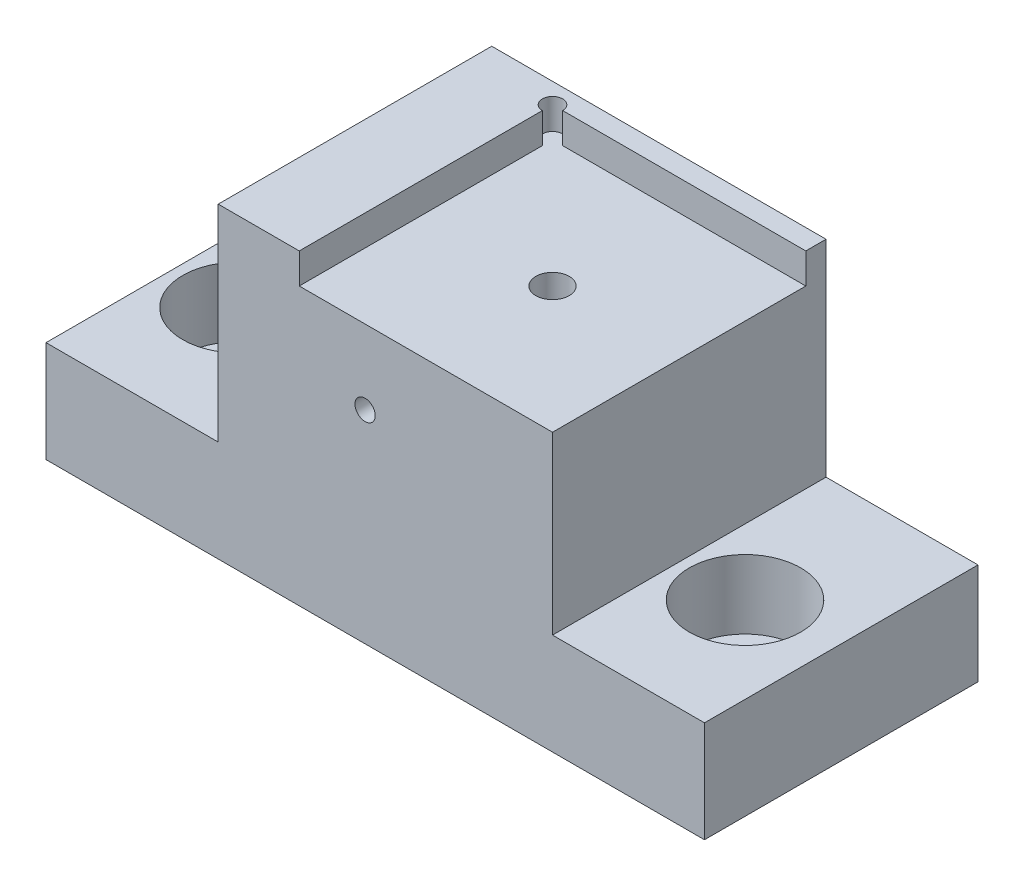
SolidWorks part; units mm, degrees
material "6061 合金"
ref_plane "前视基准面" through (0, 0, 0) normal (0, 0, 1) x (1, 0, 0)
ref_plane "上视基准面" through (0, 0, 0) normal (0, 1, 0) x (1, 0, 0)
ref_plane "右视基准面" through (0, 0, 0) normal (1, 0, 0) x (0, 0, -1)
sketch "草图1" plane through (0, 0, 0) normal (0, 1, 0) x (1, 0, 0)
  line L1 (-14.5, 14.5) -> (14.5, 14.5)
  line L2 (-14.5, 14.5) -> (-14.5, -14.5)
  line L3 (-14.5, -14.5) -> (14.5, -14.5)
  line L4 (14.5, 14.5) -> (14.5, -14.5)
  line L5 (-14.5, 14.5) -> (14.5, -14.5) construction
  line L6 (-14.5, -14.5) -> (14.5, 14.5) construction
  point P0 (0, 0)
  dimension "D1" = 29
  dimension "D2" = 29
extrude "凸台-拉伸1" add sketch "草图1" along normal blind 5
sketch "草图2" plane through (0, 5, 0) normal (0, -1, 0) x (1, 0, 0)
  line L1 (-12.5, 12.5) -> (12.5, 12.5)
  line L2 (-12.5, 12.5) -> (-12.5, -12.5)
  line L3 (-12.5, -12.5) -> (12.5, -12.5)
  line L4 (12.5, 12.5) -> (12.5, -12.5)
  line L5 (-12.5, 12.5) -> (12.5, -12.5) construction
  line L6 (-12.5, -12.5) -> (12.5, 12.5) construction
  point P0 (0, 0)
  dimension "D1" = 25
  dimension "D2" = 25
extrude "切除-拉伸1" cut sketch "草图2" along normal blind 3
sketch "草图3" plane through (0, 0, 0) normal (0, -1, 0) x (-1, 0, 0)
  line L1 (-14.5, -14.5) -> (20.5, -14.5)
  line L2 (-14.5, -14.5) -> (-14.5, 14.5)
  line L3 (-14.5, 14.5) -> (20.5, 14.5)
  line L4 (20.5, -14.5) -> (20.5, 14.5)
  dimension "D1" = 29
  dimension "D2" = 35
extrude "拉到底部滑块" add sketch "草图3" along normal up to surface (25.3412 mm away)
sketch "草图5" plane through (0, 2, 0) normal (0, 1, 0) x (1, 0, 0)
  circle A0 centre (0, 0) radius 2.1526
hole_wizard "M4 螺纹孔1" positions "3D草图1" profile "草图6" tap size "M4" standard "GB"
sketch3d "3D草图1"
  point P0 (0, 2, 0)
sketch "草图6" plane through (0, 2, 0) normal (1, 0, 0) x (0, 0, 1)
  line L0 (0, 0) -> (0, 11.0914)
  line L1 (0, 11.0914) -> (1.65, 10.1)
  line L2 (1.65, 10.1) -> (1.65, 0)
  line L5 (1.65, 0) -> (0, 0)
  line L10 (0, 11.0914) -> (-1.65, 10.1) construction
  line L11 (0, -6.35) -> (0, 107.95) construction
  dimension "螺纹孔钻头直径" = 3.3
  dimension "螺纹孔钻头深度" = 10.1
  dimension "导头角度" = 118
cosmetic thread "孔螺蚊线1" parameters "D1"=8, "D2"=4
sketch "草图9" plane through (0, 5, 0) normal (0, 1, 0) x (1, 0, 0)
  circle A0 centre (-12.5, 12.5) radius 1
extrude "切除-拉伸2" cut sketch "草图9" against normal up to surface (3 mm away) up to face at (0, 2, 1.65)
sketch "草图11" plane through (-14.5, 0, 0) normal (-1, 0, 0) x (0, 0, 1)
  line L4 (-14.5, 0) -> (14.5, 0)
  line L5 (14.5, 0) -> (14.5, 5)
  line L6 (14.5, 5) -> (-14.5, 5)
  line L7 (-14.5, 5) -> (-14.5, 0)
  line L8 (-14.5, 0) -> (14.5, 0)
  line L9 (14.5, 0) -> (14.5, 5)
  line L10 (14.5, 5) -> (-14.5, 5)
  line L11 (-14.5, 5) -> (-14.5, 0)
  dimension "D1" = 0
extrude "凸台-拉伸4" add sketch "草图11" along normal up to surface (6 mm away) up to face at (-20.5, -12.6706, 0)
sketch "草图17" plane through (0, 5, 0) normal (0, 1, 0) x (1, 0, 0)
  line L0 (-20.5, -14.5) -> (14.5, -14.5) construction
  line L1 (14.5, -14.5) -> (14.5, 14.5) construction
  line L2 (-20.5, -14.5) -> (14.5, -14.5)
  line L3 (14.5, -14.5) -> (14.5, 14.5)
  line L4 (-20.5, -12.5) -> (12.5, -12.5)
  line L5 (12.5, -12.5) -> (12.5, 14.5)
  line L6 (12.5, 14.5) -> (14.5, 14.5)
  line L7 (-20.5, -12.5) -> (-20.5, -14.5)
  dimension "D1" = 2
extrude "切除-拉伸8" cut sketch "草图17" against normal through all
sketch "草图18" plane through (0, -25.3412, 0) normal (0, -1, 0) x (1, 0, 0)
  line L0 (0, 0) -> (-6, 0) construction
  line L1 (16.5, 0) -> (-16.5, 0) construction
  line L2 (-6, 0) -> (-6, 12.5) construction
  line L3 (12.5, 12.5) -> (-20.5, 12.5) construction
  circle A0 centre (-6, 0) radius 1.512
  dimension "D1" = 6
sketch "草图19" plane through (0, -25.3412, 0) normal (0, -1, 0) x (-1, 0, 0)
  line L0 (-12.5, -12.5) -> (20.5, -12.5) construction
  line L1 (46, -12.5) -> (-34, -12.5)
  line L2 (46, -12.5) -> (46, 12.5)
  line L3 (46, 12.5) -> (-34, 12.5)
  line L4 (-34, -12.5) -> (-34, 12.5)
  line L5 (46, -12.5) -> (-34, 12.5) construction
  line L6 (46, 12.5) -> (-34, -12.5) construction
  point P0 (6, 0)
  dimension "D1" = 80
extrude "凸台-拉伸5" add sketch "草图19" against normal blind 10
sketch "草图21" plane through (0, -15.3412, 0) normal (0, 1, 0) x (1, 0, 0)
  line L0 (-6, 0) -> (-31, 0)
  line L3 (-16.5, 0) -> (16.5, 0) construction
  line L4 (-6, 0) -> (19, 0)
  dimension "D1" = 25
  dimension "D2" = 25
hole_wizard "打孔尺寸(%根据)内六角圆柱头螺钉的类型1" positions "3D草图2" profile "草图22" counterbore size "M6" standard "GB"
sketch3d "3D草图2"
  point P0 (-31, -15.3412, 0)
  point P3 (19, -15.3412, 0)
sketch "草图22" plane through (-31, -15.3412, 0) normal (1, 0, 0) x (0, 0, 1)
  line L0 (0, 0) -> (0, 12.0828)
  line L1 (0, 12.0828) -> (3.3, 10.1)
  line L2 (3.3, 10.1) -> (3.3, 6.8)
  line L3 (3.3, 6.8) -> (5.5, 6.8)
  line L4 (5.5, 6.8) -> (5.5, 0)
  line L5 (5.5, 0) -> (0, 0)
  line L10 (0, 12.0828) -> (-3.3, 10.1) construction
  line L11 (0, -6.35) -> (0, 107.95) construction
  dimension "孔直径" = 6.6
  dimension "孔深度" = 10.1
  dimension "柱形沉头孔直径" = 11
  dimension "柱形沉头孔深度" = 6.8
  dimension "导头角度" = 118
sketch "草图23" plane through (0, 0, -12.5) normal (0, 0, -1) x (-1, 0, 0)
  line L1 (-34, -15.3412) -> (46, -15.3412)
  line L2 (-34, -15.3412) -> (-34, -25.3412)
  line L3 (-34, -25.3412) -> (46, -25.3412)
  line L4 (46, -15.3412) -> (46, -25.3412)
extrude "凸台-拉伸6" add sketch "草图23" along normal up to surface (2 mm away) up to face at (-4, -10.1706, -14.5)
sketch "草图24" plane through (-46, 0, 0) normal (-1, 0, 0) x (0, 0, 1)
  line L4 (-14.5, -25.3412) -> (12.5, -25.3412)
  line L5 (12.5, -25.3412) -> (12.5, -15.3412)
  line L6 (12.5, -15.3412) -> (-14.5, -15.3412)
  line L7 (-14.5, -15.3412) -> (-14.5, -25.3412)
  line L8 (-14.5, -25.3412) -> (12.5, -25.3412)
  line L9 (12.5, -25.3412) -> (12.5, -15.3412)
  line L10 (12.5, -15.3412) -> (-14.5, -15.3412)
  line L11 (-14.5, -15.3412) -> (-14.5, -25.3412)
  dimension "D1" = 0
extrude "切除-拉伸9" cut sketch "草图24" against normal blind 2
sketch "草图25" plane through (0, -25.3412, 0) normal (0, -1, 0) x (1, 0, 0)
  line L0 (-31, 0) -> (-21, 0) construction
  line L1 (-6, 0) -> (-31, 0) construction
  line L2 (19, 0) -> (9, 0) construction
  line L3 (-6, 0) -> (19, 0) construction
  dimension "D1" = 10
hole_wizard "大小mm 暗销孔1" positions "3D草图3" profile "草图26" hole size "Ø4.0" standard "GB"
sketch3d "3D草图3"
  point P0 (-21, -25.3412, 0)
sketch "草图26" plane through (-21, -25.3412, 0) normal (1, 0, 0) x (0, 0, -1)
  line L0 (0, 0) -> (0, 6.2017)
  line L1 (0, 6.2017) -> (2, 5)
  line L2 (2, 5) -> (2, 0)
  line L5 (2, 0) -> (0, 0)
  line L10 (0, 6.2017) -> (-2, 5) construction
  line L11 (0, -6.35) -> (0, 107.95) construction
  dimension "孔直径" = 4
  dimension "孔深度" = 5
  dimension "导头角度" = 118
sketch "草图27" plane through (0, -25.3412, 0) normal (0, -1, 0) x (1, 0, 0)
  line L0 (8.5, 0) -> (9.5, 0) construction
  line L1 (8.5, 2) -> (9.5, 2)
  line L2 (8.5, -2) -> (9.5, -2)
  arc A0 (8.5, 2) -> (8.5, -2) centre (8.5, 0) ccw
  arc A1 (9.5, -2) -> (9.5, 2) centre (9.5, 0) ccw
  circle A2 centre (-21, 0) radius 2 construction
  point P2 (9, 0)
  dimension "D1" = 1
extrude "切除-拉伸10" cut sketch "草图27" against normal blind 5
sketch "草图28" plane through (0, 0, 12.5) normal (0, 0, 1) x (1, 0, 0)
  line L0 (-6, -25.3412) -> (-6, -5.3412) construction
  circle A0 centre (-6, -5.3412) radius 1
  dimension "D1" = 20
extrude "切除-拉伸11" cut sketch "草图28" against normal blind 2
hole_wizard "M6 螺纹孔1" positions "3D草图4" profile "草图29" tap size "M6" standard "GB"
sketch3d "3D草图4"
  point P0 (-6, -25.3412, 0)
sketch "草图29" plane through (-6, -25.3412, 0) normal (1, 0, 0) x (0, 0, -1)
  line L0 (0, 0) -> (0, 11.5022)
  line L1 (0, 11.5022) -> (2.5, 10)
  line L2 (2.5, 10) -> (2.5, 0)
  line L5 (2.5, 0) -> (0, 0)
  line L10 (0, 11.5022) -> (-2.5, 10) construction
  line L11 (0, -6.35) -> (0, 107.95) construction
  dimension "螺纹孔钻头直径" = 5
  dimension "螺纹孔钻头深度" = 10
  dimension "导头角度" = 118
cosmetic thread "孔螺蚊线2" parameters "D1"=10, "D2"=6
sketch "草图30" plane through (0, -25.3412, 0) normal (0, -1, 0) x (-1, 0, 0)
  circle A0 centre (21, 0) radius 2
  circle A1 centre (-9, 0) radius 2
extrude "切除-拉伸12" cut sketch "草图31" against normal through all and the other way through all
sketch "草图31" plane through (-6.0032, 14.6588, 10.4718) normal (0, 0, 1) x (1, 0, 0)
  line L13 (10.1171, -31.7) -> (8.8541, -31.7)
  line L14 (8.8541, -31.7) -> (6.0752, -36.5641)
  line L15 (6.0752, -36.5641) -> (6.5318, -36.825)
  line L16 (6.5318, -36.825) -> (10.275, -36.825)
  line L17 (10.275, -38.325) -> (9.525, -38.325)
  line L18 (9.525, -38.325) -> (9.525, -40)
  line L19 (-9.7761, -40) -> (-9.7761, -38.0744)
  line L20 (-9.7761, -38.0744) -> (-10.5261, -38.0744)
  line L21 (-10.5261, -36.5744) -> (-6.5013, -36.5744)
  line L22 (-6.5013, -36.5744) -> (-6.5013, -36.3244)
  line L23 (-6.5013, -36.3244) -> (-9.1432, -31.7)
  line L24 (-9.1432, -31.7) -> (-10.3692, -31.7)
  line L25 (-10.3692, -30.2) -> (10.1171, -30.2)
  line L26 (-9.7761, -40) -> (9.525, -40)
  arc A4 (10.1171, -31.7) -> (10.1171, -30.2) centre (10.1171, -30.95) ccw
  arc A5 (10.275, -38.325) -> (10.275, -36.825) centre (10.275, -37.575) ccw
  arc A6 (-10.5261, -36.5744) -> (-10.5261, -38.0744) centre (-10.5261, -37.3244) ccw
  arc A7 (-10.3692, -30.2) -> (-10.3692, -31.7) centre (-10.3692, -30.95) ccw
sketch "草图32" plane through (-44, 0, 0) normal (-1, 0, 0) x (0, 0, 1)
  line L4 (-14.5, -15.3412) -> (-14.5, -25.3412)
  line L5 (-14.5, -25.3412) -> (12.5, -25.3412)
  line L6 (12.5, -25.3412) -> (12.5, -15.3412)
  line L7 (12.5, -15.3412) -> (-14.5, -15.3412)
  line L8 (-14.5, -15.3412) -> (-14.5, -25.3412)
  line L9 (-14.5, -25.3412) -> (12.5, -25.3412)
  line L10 (12.5, -25.3412) -> (12.5, -15.3412)
  line L11 (12.5, -15.3412) -> (-14.5, -15.3412)
  dimension "D1" = 0
extrude "切除-拉伸13" cut sketch "草图32" against normal blind 6.5
sketch "草图33" plane through (34, 0, 0) normal (1, 0, 0) x (0, 0, -1)
  line L4 (-12.5, -25.3412) -> (14.5, -25.3412)
  line L5 (14.5, -25.3412) -> (14.5, -15.3412)
  line L6 (14.5, -15.3412) -> (-12.5, -15.3412)
  line L7 (-12.5, -15.3412) -> (-12.5, -25.3412)
  line L8 (-12.5, -25.3412) -> (14.5, -25.3412)
  line L9 (14.5, -25.3412) -> (14.5, -15.3412)
  line L10 (14.5, -15.3412) -> (-12.5, -15.3412)
  line L11 (-12.5, -15.3412) -> (-12.5, -25.3412)
  dimension "D1" = 0
extrude "切除-拉伸14" cut sketch "草图33" against normal blind 6.5
sketch "草图34" plane through (0, -25.3412, 0) normal (0, -1, 0) x (1, 0, 0)
  line L0 (-21, 0) -> (-21, -8) construction
  line L2 (9, -8) -> (9, 0) construction
  line L4 (-21, 0) -> (-21, 8) construction
  circle A0 centre (-21, -8) radius 2
  circle A1 centre (9, -8) radius 2
  circle A2 centre (-21, 8) radius 2
sketch "草图35" plane through (0, -25.3412, 0) normal (0, -1, 0) x (1, 0, 0)
  line L0 (8.5, -8) -> (9.5, -8) construction
  line L2 (8.5, -6) -> (9.5, -6)
  line L3 (8.5, -10) -> (9.5, -10)
  line L4 (9, -8) -> (9, 0) construction
  arc A0 (8.5, -6) -> (8.5, -10) centre (8.5, -8) ccw
  arc A1 (9.5, -10) -> (9.5, -6) centre (9.5, -8) ccw
  circle A2 centre (-21, 0) radius 2 construction
  point P5 (9, -8)
  dimension "D1" = 1
extrude "切除-拉伸15" cut sketch "草图35" against normal up to surface (5 mm away) up to face at (9, -20.3412, 0)
hole_wizard "大小mm 暗销孔2" positions "3D草图5" profile "草图36" hole size "Ø4.0" standard "GB"
sketch3d "3D草图5"
  point P0 (-21, -25.3412, -8)
sketch "草图36" plane through (-21, -25.3412, -8) normal (1, 0, 0) x (0, 0, -1)
  line L0 (0, 0) -> (0, 6.2017)
  line L1 (0, 6.2017) -> (2, 5)
  line L2 (2, 5) -> (2, 0)
  line L5 (2, 0) -> (0, 0)
  line L10 (0, 6.2017) -> (-2, 5) construction
  line L11 (0, -6.35) -> (0, 107.95) construction
  dimension "孔直径" = 4
  dimension "孔深度" = 5
  dimension "导头角度" = 118
hole_wizard "大小mm 暗销孔3" positions "3D草图6" profile "草图37" hole size "Ø4.0" standard "GB"
sketch3d "3D草图6"
  point P0 (-21, -25.3412, 8)
sketch "草图37" plane through (-21, -25.3412, 8) normal (1, 0, 0) x (0, 0, -1)
  line L0 (0, 0) -> (0, 6.2017)
  line L1 (0, 6.2017) -> (2, 5)
  line L2 (2, 5) -> (2, 0)
  line L5 (2, 0) -> (0, 0)
  line L10 (0, 6.2017) -> (-2, 5) construction
  line L11 (0, -6.35) -> (0, 107.95) construction
  dimension "孔直径" = 4
  dimension "孔深度" = 5
  dimension "导头角度" = 118
sketch "草图38" plane through (0, 0, 12.5) normal (0, 0, 1) x (1, 0, 0)
  line L0 (-15.7793, -25.3412) -> (-37.5, -25.3412) construction
  line L1 (-18.4091, -25.3412) -> (5.5528, -25.3412)
  line L2 (-18.4091, -25.3412) -> (-18.4091, -11.5018)
  line L3 (-18.4091, -11.5018) -> (5.5528, -11.5018)
  line L4 (5.5528, -25.3412) -> (5.5528, -11.5018)
extrude "凸台-拉伸7" add sketch "草图38" against normal up to surface (27 mm away) up to face at (-5.625, -18.3798, -14.5)
